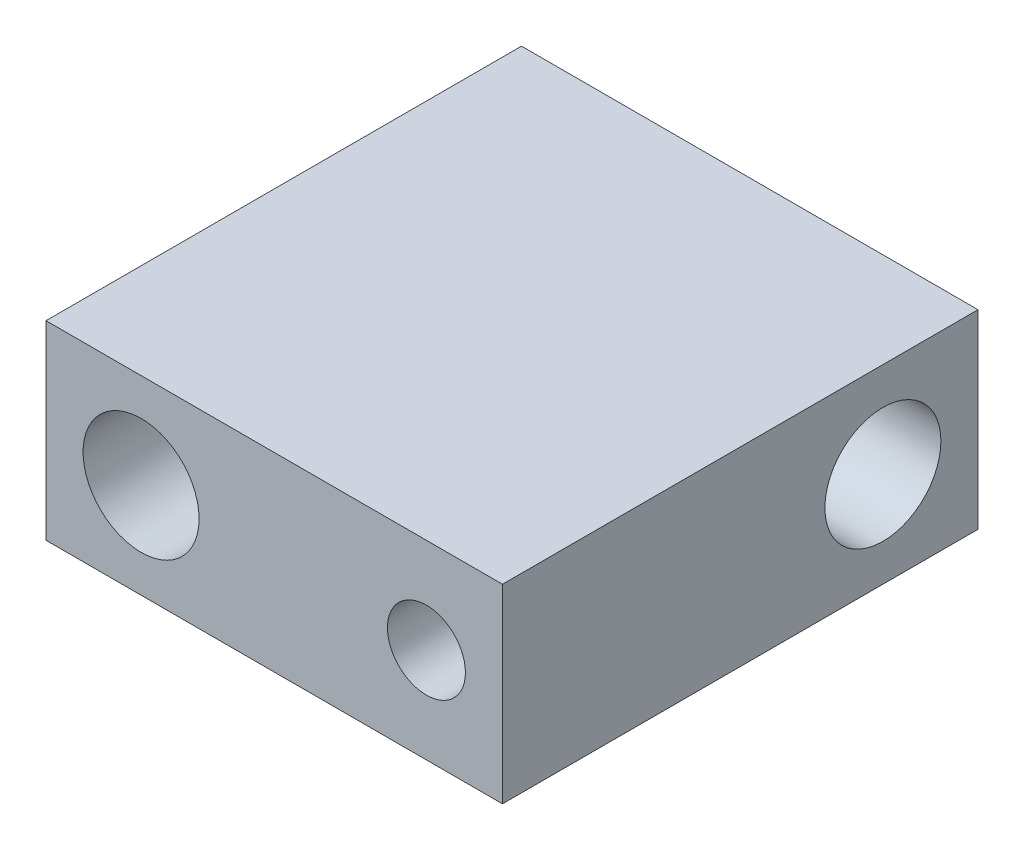
SolidWorks part; units mm, degrees
ref_plane "Front Plane" through (0, 0, 0) normal (0, 0, 1) x (1, 0, 0)
ref_plane "Top Plane" through (0, 0, 0) normal (0, 1, 0) x (1, 0, 0)
ref_plane "Right Plane" through (0, 0, 0) normal (1, 0, 0) x (0, 0, -1)
sketch "Sketch1" plane through (0, 0, 0) normal (0, 0, 1) x (1, 0, 0)
  line L1 (-24, 10) -> (24, 10)
  line L2 (-24, 10) -> (-24, -10)
  line L3 (-24, -10) -> (24, -10)
  line L4 (24, 10) -> (24, -10)
  line L5 (-24, 10) -> (24, -10) construction
  line L6 (-24, -10) -> (24, 10) construction
  circle A0 centre (-14, 0) radius 6.1
  circle A1 centre (16, 0) radius 4.1
  point P0 (0, 0)
  dimension "D3" = 12.2
  dimension "D4" = 10
  dimension "D5" = 8.2
  dimension "D6" = 8
  dimension "D1" = 20
  dimension "D2" = 48
extrude "Boss-Extrude1" add sketch "Sketch1" along normal blind 30
sketch "Sketch2" plane through (0, 0, 0) normal (0, 0, -1) x (-1, 0, 0)
  line L1 (-24, 10) -> (24, 10)
  line L2 (-24, 10) -> (-24, -10)
  line L3 (-24, -10) -> (24, -10)
  line L4 (24, 10) -> (24, -10)
extrude "Boss-Extrude2" add sketch "Sketch2" along normal blind 20
sketch "Sketch3" plane through (24, 0, 0) normal (1, 0, 0) x (0, 0, -1)
  line L0 (20, 10) -> (20, -10) construction
  circle A0 centre (10, 0) radius 6.1
  dimension "D1" = 12.2
  dimension "D2" = 10
extrude "Cut-Extrude1" cut sketch "Sketch3" against normal blind 40
